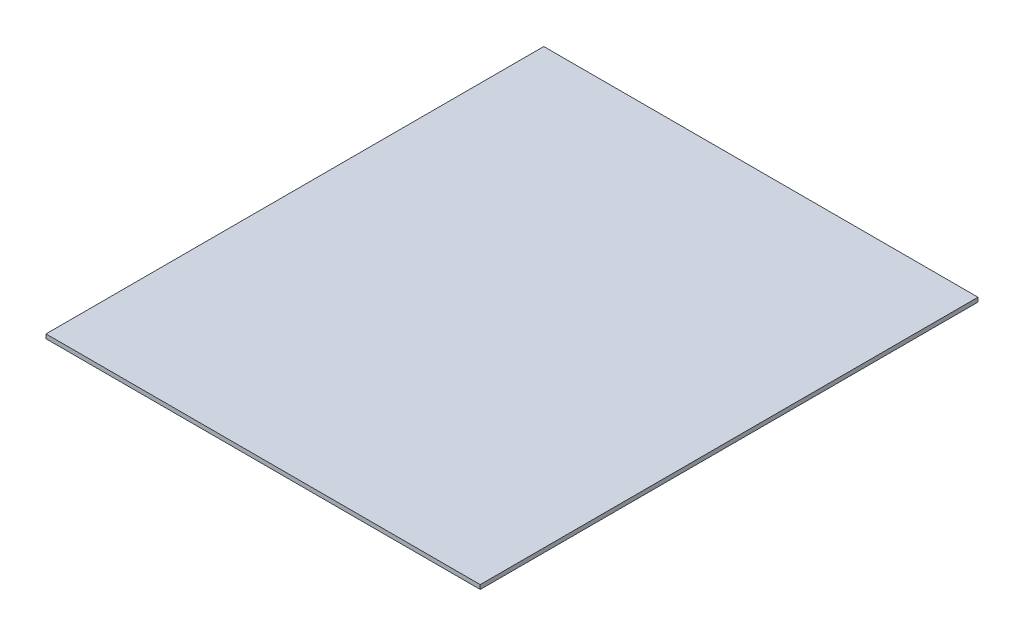
SolidWorks part; units mm, degrees
ref_plane "Front Plane" through (0, 0, 0) normal (0, 0, 1) x (1, 0, 0)
ref_plane "Top Plane" through (0, 0, 0) normal (0, 1, 0) x (1, 0, 0)
ref_plane "Right Plane" through (0, 0, 0) normal (1, 0, 0) x (0, 0, -1)
sketch "Sketch1" plane through (0, 0, 0) normal (0, 1, 0) x (1, 0, 0)
  line L1 (-205, 235) -> (205, 235)
  line L2 (-205, 235) -> (-205, -235)
  line L3 (-205, -235) -> (205, -235)
  line L4 (205, 235) -> (205, -235)
  line L5 (-205, 235) -> (205, -235) construction
  line L6 (-205, -235) -> (205, 235) construction
  point P0 (0, 0)
  dimension "D1" = 410
  dimension "D2" = 470
extrude "Boss-Extrude1" add sketch "Sketch1" along normal blind 4
